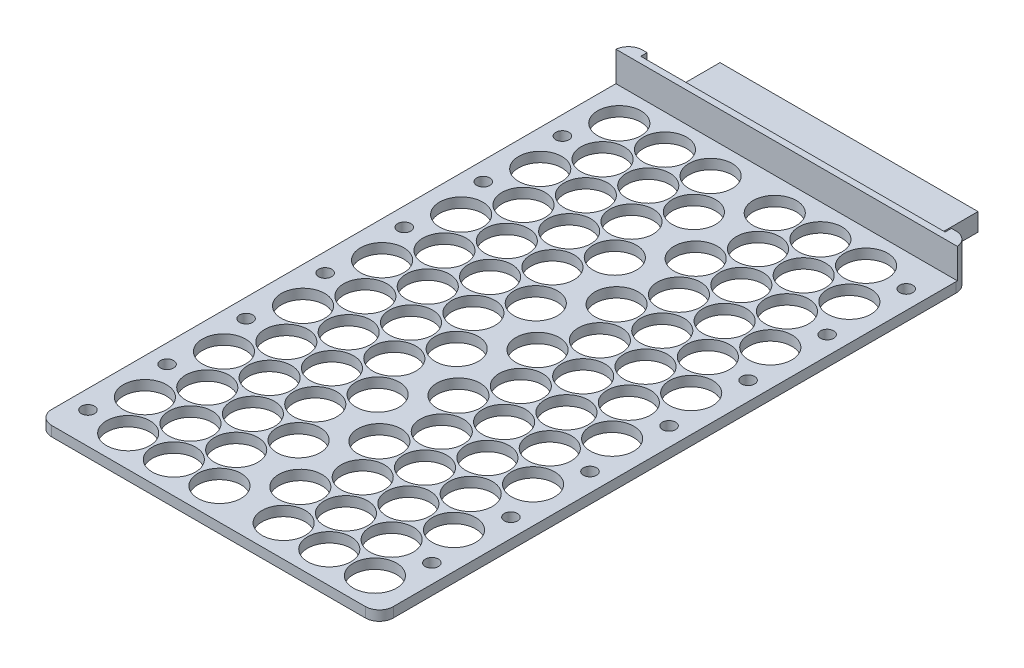
SolidWorks part; units mm, degrees
material "Nylon 6/10"
ref_plane "Front Plane" through (0, 0, 0) normal (0, 0, 1) x (1, 0, 0)
ref_plane "Top Plane" through (0, 0, 0) normal (0, 1, 0) x (1, 0, 0)
ref_plane "Right Plane" through (0, 0, 0) normal (1, 0, 0) x (0, 0, -1)
sketch "Sketch2" plane through (0, 0, 0) normal (0, 1, 0) x (1, 0, 0)
  line L1 (0, 0) -> (171.7, 0)
  line L2 (0, 0) -> (0, 290.6287)
  line L3 (0, 290.6287) -> (171.7, 290.6287)
  line L4 (171.7, 0) -> (171.7, 290.6287)
  dimension "D1" = 171.7
  dimension "D2" = 290.6287
extrude "Boss-Extrude6" add sketch "Sketch2" along normal blind 5
sketch "Sketch1" plane through (0, 0, 0) normal (0, 1, 0) x (1, 0, 0)
  line L1 (0, 0) -> (171.7029, 0)
  line L2 (0, 0) -> (0, 290.6287)
  line L3 (0, 290.6287) -> (171.7029, 290.6287)
  line L4 (171.7029, 0) -> (171.7029, 290.6287)
  line L5 (29.5647, 15.875) -> (18.0897, 35.7503) construction
  line L6 (18.0897, 35.7503) -> (18.0897, 15.875) construction
  line L7 (18.0897, 15.875) -> (29.5647, 15.875) construction
  line L8 (29.5647, 55.6256) -> (18.0897, 35.7503) construction
  line L9 (18.0897, 35.7503) -> (29.5647, 35.7503) construction
  line L10 (29.5647, 35.7503) -> (29.5647, 55.6256) construction
  line L11 (29.5647, 55.6256) -> (0, 55.6256) construction
  line L12 (0, 55.6256) -> (18.0897, 75.5008) construction
  line L13 (142.1382, 35.7503) -> (171.7029, 35.7503) construction
  line L14 (171.7029, 35.7503) -> (153.6132, 15.875) construction
  circle A1 centre (29.5647, 15.875) radius 10.875
  circle A2 centre (18.0897, 35.7503) radius 10.875
  circle A3 centre (41.0397, 35.7503) radius 10.875
  circle A4 centre (52.5147, 15.875) radius 10.875
  circle A5 centre (63.9897, 35.7503) radius 10.875
  circle A6 centre (75.4647, 15.875) radius 10.875
  circle A43 centre (96.2382, 35.7503) radius 10.875
  circle A44 centre (119.1882, 35.7503) radius 10.875
  circle A45 centre (142.1382, 35.7503) radius 10.875
  circle A46 centre (153.6132, 15.875) radius 10.875
  circle A47 centre (130.6632, 15.875) radius 10.875
  circle A48 centre (107.7132, 15.875) radius 10.875
  circle A49 centre (96.2382, 75.5008) radius 10.875
  circle A50 centre (119.1882, 75.5008) radius 10.875
  circle A51 centre (142.1382, 75.5008) radius 10.875
  circle A52 centre (153.6132, 55.6256) radius 10.875
  circle A53 centre (130.6632, 55.6256) radius 10.875
  circle A54 centre (107.7132, 55.6256) radius 10.875
  circle A55 centre (96.2382, 115.2514) radius 10.875
  circle A56 centre (119.1882, 115.2514) radius 10.875
  circle A57 centre (142.1382, 115.2514) radius 10.875
  circle A58 centre (153.6132, 95.3761) radius 10.875
  circle A59 centre (130.6632, 95.3761) radius 10.875
  circle A60 centre (107.7132, 95.3761) radius 10.875
  circle A61 centre (96.2382, 155.002) radius 10.875
  circle A62 centre (119.1882, 155.002) radius 10.875
  circle A63 centre (142.1382, 155.002) radius 10.875
  circle A64 centre (153.6132, 135.1267) radius 10.875
  circle A65 centre (130.6632, 135.1267) radius 10.875
  circle A66 centre (107.7132, 135.1267) radius 10.875
  circle A67 centre (96.2382, 194.7525) radius 10.875
  circle A68 centre (119.1882, 194.7525) radius 10.875
  circle A69 centre (142.1382, 194.7525) radius 10.875
  circle A70 centre (153.6132, 174.8773) radius 10.875
  circle A71 centre (130.6632, 174.8773) radius 10.875
  circle A72 centre (107.7132, 174.8773) radius 10.875
  circle A73 centre (96.2382, 234.5031) radius 10.875
  circle A74 centre (119.1882, 234.5031) radius 10.875
  circle A75 centre (142.1382, 234.5031) radius 10.875
  circle A76 centre (153.6132, 214.6278) radius 10.875
  circle A77 centre (130.6632, 214.6278) radius 10.875
  circle A78 centre (107.7132, 214.6278) radius 10.875
  circle A79 centre (96.2382, 274.2537) radius 10.875
  circle A80 centre (119.1882, 274.2537) radius 10.875
  circle A81 centre (142.1382, 274.2537) radius 10.875
  circle A82 centre (153.6132, 254.3784) radius 10.875
  circle A83 centre (130.6632, 254.3784) radius 10.875
  circle A84 centre (107.7132, 254.3784) radius 10.875
  circle A127 centre (18.0897, 75.5008) radius 10.875
  circle A128 centre (41.0397, 75.5008) radius 10.875
  circle A129 centre (63.9897, 75.5008) radius 10.875
  circle A130 centre (75.4647, 55.6256) radius 10.875
  circle A131 centre (52.5147, 55.6256) radius 10.875
  circle A132 centre (29.5647, 55.6256) radius 10.875
  circle A133 centre (18.0897, 115.2514) radius 10.875
  circle A134 centre (41.0397, 115.2514) radius 10.875
  circle A135 centre (63.9897, 115.2514) radius 10.875
  circle A136 centre (75.4647, 95.3761) radius 10.875
  circle A137 centre (52.5147, 95.3761) radius 10.875
  circle A138 centre (29.5647, 95.3761) radius 10.875
  circle A139 centre (18.0897, 155.002) radius 10.875
  circle A140 centre (41.0397, 155.002) radius 10.875
  circle A141 centre (63.9897, 155.002) radius 10.875
  circle A142 centre (75.4647, 135.1267) radius 10.875
  circle A143 centre (52.5147, 135.1267) radius 10.875
  circle A144 centre (29.5647, 135.1267) radius 10.875
  circle A145 centre (18.0897, 194.7525) radius 10.875
  circle A146 centre (41.0397, 194.7525) radius 10.875
  circle A147 centre (63.9897, 194.7525) radius 10.875
  circle A148 centre (75.4647, 174.8773) radius 10.875
  circle A149 centre (52.5147, 174.8773) radius 10.875
  circle A150 centre (29.5647, 174.8773) radius 10.875
  circle A151 centre (18.0897, 234.5031) radius 10.875
  circle A152 centre (41.0397, 234.5031) radius 10.875
  circle A153 centre (63.9897, 234.5031) radius 10.875
  circle A154 centre (75.4647, 214.6278) radius 10.875
  circle A155 centre (52.5147, 214.6278) radius 10.875
  circle A156 centre (29.5647, 214.6278) radius 10.875
  circle A157 centre (18.0897, 274.2537) radius 10.875
  circle A158 centre (41.0397, 274.2537) radius 10.875
  circle A159 centre (63.9897, 274.2537) radius 10.875
  circle A160 centre (75.4647, 254.3784) radius 10.875
  circle A161 centre (52.5147, 254.3784) radius 10.875
  circle A162 centre (29.5647, 254.3784) radius 10.875
  dimension "D1" = 21.75
  dimension "D2" = 15.875
  dimension "D3" = 22.95
  dimension "D5" = 60
  dimension "D8" = 22.95
  dimension "D9" = 22.95
  dimension "D10" = 60
  dimension "D13" = 28.75
  dimension "D4" = 16.375
  dimension "D16" = 26.875
  dimension "D14" = 26.875
  dimension "D6" = 3
  dimension "D7" = 1
  dimension "D11" = 2
  dimension "D12" = 7
extrude "Cut-Extrude1" cut sketch "Sketch1" along normal blind 7 contours A47 | A46 | A45 | A44 | A43 | A54 | A53 | A52 | A51 | A50 | A49 | A60 | A59 | A58 | A57 | A56 | A55 | A66 | A65 | A64 | A63 | A62 | A61 | A72 | A67 | A78 | A73 | A84 | A79 | A80 | A81 | A82 | A83 | A74 | A75 | A77 | A76 | A69 | A70 | A71 | A68 | A159 | A158 | A157 | A162 | A161 | A160 | A153 | A152 | A156 | A151 | A155 | A154 | A147 | A146 | A145 | A148 | A141 | A149 | A150 | A140 | A142 | A143 | A144 | A139 | A133 | A134 | A135 | A136 | A137 | A138 | A128 | A127 | A129 | A130 | A131 | A132 | A2 | A3 | A5 | A6 | A4 | A1 | A48
sketch "Sketch5" plane through (0, 5, 0) normal (0, 1, 0) x (1, 0, 0)
  line L0 (9.3449, 254.3784) -> (18.0897, 274.2537) construction
  line L1 (9.3449, 254.3784) -> (0, 254.3784) construction
  line L2 (18.0897, 234.5031) -> (9.3449, 254.3784) construction
  line L3 (18.6897, 254.3784) -> (9.3449, 254.3784) construction
  line L4 (142.1382, 75.5008) -> (162.3566, 75.5008) construction
  line L5 (0, 290.6287) -> (0, 0) construction
  line L6 (162.3566, 35.7503) -> (171.7, 35.7503) construction
  line L7 (153.6132, 15.875) -> (162.3566, 35.7503) construction
  line L8 (162.3566, 35.7503) -> (153.6132, 55.6256) construction
  line L9 (171.7, 0) -> (171.7, 290.6287) construction
  line L10 (162.3566, 35.7503) -> (153.0132, 35.7503) construction
  line L12 (29.5647, 214.6278) -> (9.3449, 214.6278) construction
  circle A1 centre (9.3449, 254.3784) radius 3.3
  circle A4 centre (162.3566, 35.7503) radius 3.3
  circle A7 centre (162.3566, 75.5008) radius 3.3
  circle A8 centre (162.3566, 115.2514) radius 3.3
  circle A9 centre (162.3566, 155.002) radius 3.3
  circle A10 centre (162.3566, 194.7525) radius 3.3
  circle A11 centre (162.3566, 234.5031) radius 3.3
  circle A12 centre (162.3566, 274.2537) radius 3.3
  circle A15 centre (9.3449, 214.6278) radius 3.3
  circle A16 centre (9.3449, 174.8773) radius 3.3
  circle A17 centre (9.3449, 135.1267) radius 3.3
  circle A18 centre (9.3449, 95.3761) radius 3.3
  circle A19 centre (9.3449, 55.6256) radius 3.3
  circle A20 centre (9.3449, 15.875) radius 3.3
  circle A21 centre (29.5647, 254.3784) radius 10.875 construction
  circle A22 centre (142.1382, 35.7503) radius 10.875 construction
  dimension "D1" = 6.6
  dimension "D2" = 6.6
  dimension "D3" = 7
  dimension "D4" = 7
extrude "Cut-Extrude3" cut sketch "Sketch5" against normal up to surface (5 mm away) up to face at (96.2382, 0, -64.6258)
sketch "Sketch12" plane through (0, 0, -290.6287) normal (0, 0, -1) x (-1, 0, 0)
  line L5 (-171.7, 5) -> (0, 5)
  line L6 (-171.7, 5) -> (-171.7, 20)
  line L7 (0, 5) -> (0, 0) construction
  line L8 (-171.7, 0) -> (0, 0)
  line L12 (-171.7, 0) -> (0, 0)
  line L13 (-171.7, 0) -> (-171.7, 5)
  line L15 (0, 0) -> (0, 5)
  line L16 (-171.7, 20) -> (0, 20)
  line L17 (-171.7, 5) -> (0, 5)
  line L26 (-171.7, 5) -> (0, 5) construction
  line L27 (0, 5) -> (0, 20)
  dimension "D1" = 15
extrude "Boss-Extrude9" add sketch "Sketch12" along normal blind 6.35
sketch "Sketch13" plane through (0, 0, -296.9787) normal (0, 0, -1) x (-1, 0, 0)
  line L1 (-162.355, 9) -> (-9.345, 9)
  line L2 (-162.355, 9) -> (-162.355, 20)
  line L3 (-162.355, 20) -> (-9.345, 20)
  line L4 (-9.345, 9) -> (-9.345, 20)
  line L8 (-162.355, 20) -> (-171.7, 20) construction
  line L10 (-171.7, 20) -> (0, 20) construction
  line L11 (-9.345, 20) -> (0, 20) construction
  dimension "D1" = 153.01
  dimension "D2" = 11
extrude "Cut-Extrude7" cut sketch "Sketch13" against normal blind 3.18
sketch "Sketch14" plane through (0, 0, -296.9787) normal (0, 0, -1) x (-1, 0, 0)
  line L6 (-171.7, 20) -> (-171.7, 0) construction
  line L7 (0, 0) -> (0, 20) construction
  line L9 (-150.7, 0) -> (-21, 0)
  line L10 (-150.7, 0) -> (-150.7, 9)
  line L11 (-150.7, 9) -> (-21, 9)
  line L12 (-21, 0) -> (-21, 9)
  line L14 (-150.7, 0) -> (-171.7, 0) construction
  line L15 (-171.7, 0) -> (0, 0) construction
  line L16 (-21, 0) -> (0, 0) construction
  line L17 (-162.355, 9) -> (-9.345, 9) construction
  dimension "D1" = 21
extrude "Boss-Extrude10" add sketch "Sketch14" along normal blind 25
fillet "Fillet1" radius 7 8 edges at (171.7, 12.5, -290.6287) (171.7, 20, -293.8037) (0, 12.5, -290.6287) (0, 20, -293.8037) (171.7, 10, -296.9787) (0, 10, -296.9787) (171.7, 2.5, 0) (0, 2.5, 0)
equation "\"cellDia\"= 21.55mm"
equation "\"cellRad\"= \"cellDia\" / 2"
equation "\"cellGap\"= 1.2mm"
equation "\"holeTol\"= .1mm"
equation "\"holeDia\"= \"cellDia\" + 2 * \"holeTol\""
equation "\"cellAngle\"= 30deg"
equation "\"groupWidth\"= \"longRailGap\" + 4 * ( \"holeDia\" + \"cellGap\" ) + \"shortRailGap\" + \"middleGapStraight\" + 2 * \"holeDia\""
equation "\"groupHeight\"= 13 * ( \"holeDia\" + \"cellGap\" ) * cos ( \"cellAngle\" ) + \"holeDia\" + \"topEdge\" + \"bottomEdge\""
equation "\"senseSpace\"= 5mm"
equation "\"outEdge\"= 0mm"
equation "\"topEdge\"= 5.5mm"
equation "\"bottomEdge\"= 5mm"
equation "\"blockWidth\"= ( 2 * \"outEdge\" ) + ( 2 * \"groupWidth\" ) + \"senseSpace\""
equation "\"blockHeight\"= \"topEdge\" + \"bottomEdge\" + \"groupHeight\" + \"BMSSpace\""
equation "\"cellLinSpace\"= \"holeDia\" + \"cellGap\""
equation "\"standThickness\"= 6"
equation "\"blockThickness\"=5"
equation "\"railThickness\"= \"blockThickness\" + \"standThickness\""
equation "\"railWidth\"= 16mm"
equation "\"boltSpacing\"= 42mm"
equation "\"nippleDia\"= 7mm"
equation "\"senseWidth\"=15.9635"
equation "\"senseHeight\"=10"
equation "\"railHeight\"= \"blockHeight\""
equation "\"sensePCBWidth\"=10.16"
equation "\"topTapWidth\"= 118mm"
equation "\"topTapHeight\"= 25mm"
equation "\"BMSBackPlateThickness\"= 3.175mm"
equation "\"BMSInset\"= 3.175mm"
equation "\"BMSSpace\"= \"BMSInset\" + \"BMSBackPlateThickness\""
equation "\"holeRad\"= \"holeDia\" / 2"
equation "\"BMSBackPlateHeight\"= 10mm"
equation "\"middleGap\"= 7mm"
equation "\"mountingHole\"= 10mm"
equation "\"D1@Sketch1\"=\"holeDia\""
equation "\"D3@Sketch1\"=\"holeDia\"+\"cellGap\""
equation "\"D8@Sketch1\"=\"holeDia\"+\"cellGap\""
equation "\"D9@Sketch1\"=\"holeDia\"+\"cellGap\""
equation "\"D13@Sketch1\"=\"holeDia\"+\"middleGap\""
equation "\"D16@Sketch1\"=\"holeRad\"+\"railWidth\""
equation "\"D2@Sketch1\"=\"holeRad\"+\"bottomEdge\""
equation "\"D4@Sketch1\"=\"holeRad\"+\"topEdge\""
equation "\"D14@Sketch1\"=\"holeRad\"+\"railWidth\""
equation "\"longRailGap\"= 18.69mm"
equation "\"shortRailGap\"= 7.21mm"
equation "\"middleGapStraight\"= 10.50mm"
equation "\"D2@Sketch2\"=\"groupHeight\""
equation "\"D1@Sketch2\"=\"groupWidth\""
equation "\"D1@Boss-Extrude6\"=\"blockThickness\""
equation "\"segmentBolts\"= 6.60mm"
equation "\"D1@Sketch5\"=\"segmentBolts\""
equation "\"D2@Sketch5\"=\"segmentBolts\""
equation "\"boltHead\"= 11mm"
equation "\"D1@Boss-Extrude9\"=\"BMSSpace\""
equation "\"BMSLength\"= 143mm"
equation "\"D1@Boss-Extrude10\"=\"topTapHeight\""
equation "\"D1@Cut-Extrude8\"=1"
equation "\"senseTop\"= 93.00mm"
equation "\"D2@Sketch13\"=\"BMSBackPlateHeight\"+1"
equation "\"D1@Sketch12\"=\"BMSBackPlateHeight\"+5"
equation "\"D2@Cell Block Sketch\"= \"blockHeight\""
